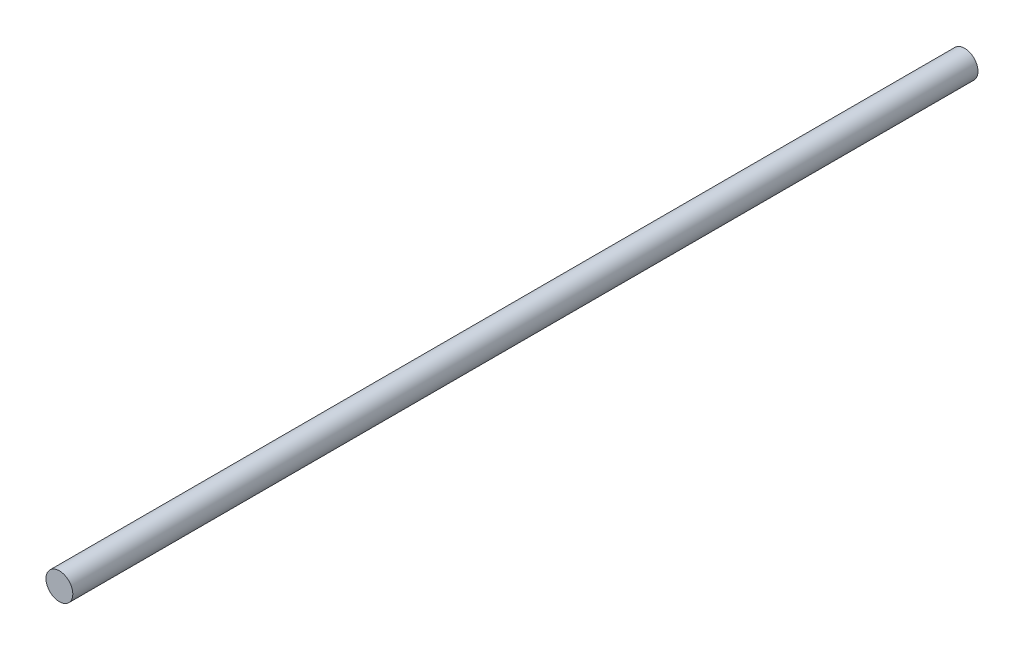
SolidWorks part; units mm, degrees
ref_plane "Front Plane" through (0, 0, 0) normal (0, 0, 1) x (1, 0, 0)
ref_plane "Top Plane" through (0, 0, 0) normal (0, 1, 0) x (1, 0, 0)
ref_plane "Right Plane" through (0, 0, 0) normal (1, 0, 0) x (0, 0, -1)
sketch "Sketch1" plane through (0, 0, 0) normal (0, 0, 1) x (1, 0, 0)
  circle A0 centre (0, 0) radius 2
  dimension "D1" = 4
extrude "Boss-Extrude1" add sketch "Sketch1" along normal blind 135
